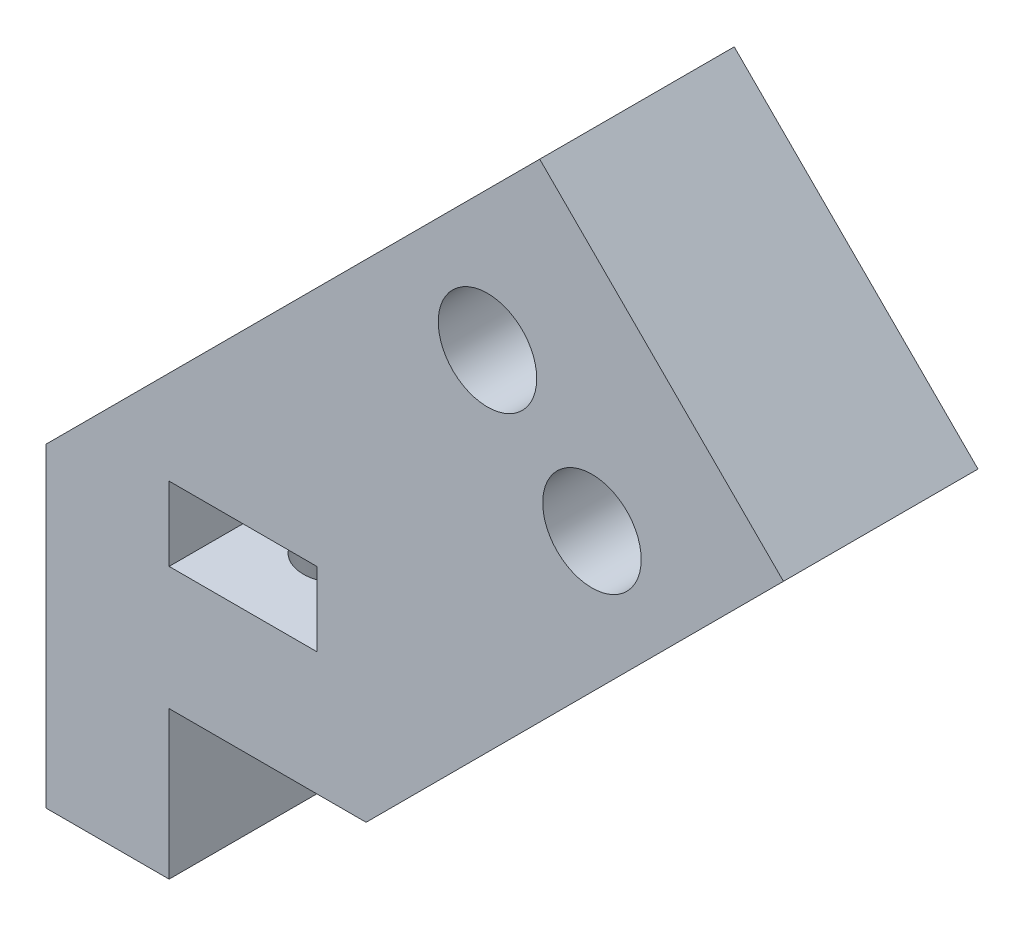
SolidWorks part; units mm, degrees
ref_plane "Front Plane" through (0, 0, 0) normal (0, 0, 1) x (1, 0, 0)
ref_plane "Top Plane" through (0, 0, 0) normal (0, 1, 0) x (1, 0, 0)
ref_plane "Right Plane" through (0, 0, 0) normal (1, 0, 0) x (0, 0, -1)
sketch "Sketch1" plane through (0, 0, 0) normal (0, 0, 1) x (1, 0, 0)
  line L0 (-30, 0) -> (-30, 6)
  line L1 (-30, 6) -> (-22, 6)
  line L2 (-30, 6) -> (0, 6) construction
  line L3 (-22, 6) -> (-5.0503, 22.9497)
  line L4 (-5.0503, 22.9497) -> (-14.9497, 32.8492)
  line L5 (-14.9497, 32.8492) -> (-35, 12.799)
  line L6 (-35, 12.799) -> (-35, 0)
  line L7 (-35, 0) -> (-30, 0)
  line L8 (8, 38) -> (8, 30) construction
  line L9 (24.8063, -16.8063) -> (-10, 18) construction
  line L10 (19.0563, -22.5563) -> (30.5563, -11.0563) construction
  line L11 (2, 43) -> (2, 38) construction
  line L12 (-11.4142, 19.4142) -> (-14.2426, 22.2426) construction
  line L13 (-18.4853, 26.4853) -> (-19.8995, 27.8995) construction
  line L14 (-10, 18) -> (-11.4142, 19.4142) construction
  line L15 (-15.6569, 23.6569) -> (-18.4853, 26.4853) construction
  line L16 (-14.2426, 22.2426) -> (-15.6569, 23.6569) construction
  circle A0 centre (-12.8284, 20.8284) radius 2
  circle A1 centre (-17.0711, 25.0711) radius 2
  dimension "D3" = 4
  dimension "D1" = 7
  dimension "D2" = 14
extrude "Boss-Extrude1" add sketch "Sketch1" against normal up to surface (7.9 mm away)
sketch "Sketch2" plane through (0, 6, 0) normal (0, -1, 0) x (1, 0, 0)
  circle A0 centre (-27, -3.95) radius 1.5
  circle A1 centre (-27, -3.95) radius 1.5 construction
  point P5 (0, 0)
extrude "Cut-Extrude1" cut sketch "Sketch2" against normal through all
sketch "Sketch3" plane through (0, 0, 0) normal (0, 0, 1) x (1, 0, 0)
  line L0 (-30, 11) -> (-24, 11)
  line L1 (-24, 11) -> (-24, 14)
  line L2 (-24, 14) -> (-30, 14)
  line L3 (-30, 14) -> (-30, 11)
  line L4 (-27, 11) -> (-27, 6) construction
  line L6 (-30, 6) -> (-22, 6) construction
  point P6 (0, 0)
  dimension "D1" = 6
  dimension "D2" = 5
  dimension "D3" = 3
extrude "Cut-Extrude2" cut sketch "Sketch3" against normal through all
